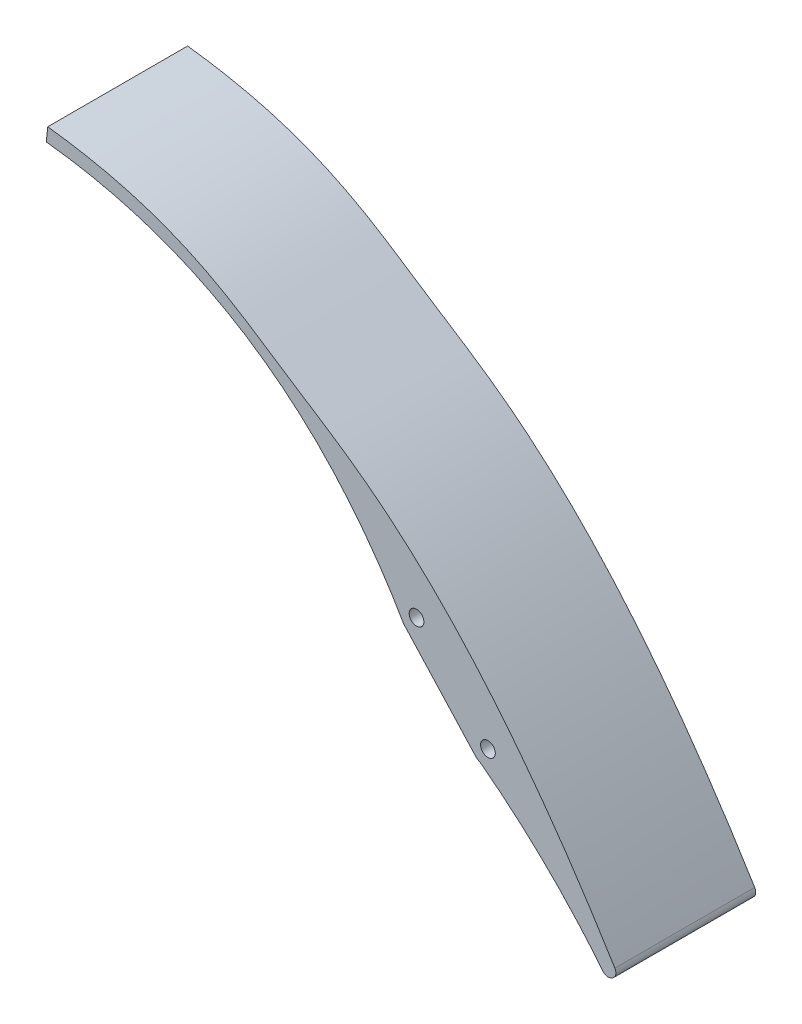
SolidWorks part; units mm, degrees
ref_plane "Front Plane" through (0, 0, 0) normal (0, 0, 1) x (1, 0, 0)
ref_plane "Top Plane" through (0, 0, 0) normal (0, 1, 0) x (1, 0, 0)
ref_plane "Right Plane" through (0, 0, 0) normal (1, 0, 0) x (0, 0, -1)
sketch "Sketch1" plane through (0, 0, 0) normal (0, 0, 1) x (1, 0, 0)
  line L0 (106.6087, -27.4995) -> (127.0352, -49.8278)
  line L2 (4.8232, 44.7408) -> (4.3944, 40.7638)
  line L4 (164.6351, -86.3417) -> (168.0847, -84.3173)
  circle A1 centre (110.2978, -24.1246) radius 5 construction
  arc A2 (127.0352, -49.8278) -> (128.7434, -51.0437) centre (130.7244, -46.4529) ccw
  circle A3 centre (0, 0) radius 43 construction
  circle A4 centre (130.7244, -46.4529) radius 1.7
  circle A5 centre (110.2978, -24.1246) radius 1.7
  spline S0 degree 2 poles (128.7434, -51.0437) (148.9684, -66.4337) (164.6351, -86.3417) knots 0 0 0 1 1 1
  spline S1 degree 3 poles (189.3837, -130.5798) (184.3453, -120.881) (179.1472, -111.2808) (168.3321, -92.3393) (162.7164, -82.997) (153.8589, -69.2518) (150.8335, -64.7151) (144.6059, -55.7509) (141.4039, -51.3233) (136.4366, -44.7833) (134.7529, -42.6197) (131.3384, -38.3486) (129.606, -36.2389) (124.3253, -29.9956) (120.6937, -25.9476) (113.1567, -18.1334) (109.2505, -14.368) (103.1437, -8.9743) (101.0669, -7.2188) (96.828, -3.7955) (94.6657, -2.128) (90.2629, 1.1268) (88.0206, 2.7142) (83.4948, 5.8371) (81.2164, 7.3742) (76.6483, 10.4306) (74.3592, 11.9509) (69.7972, 15.0169) (67.5211, 16.5576) (62.9312, 19.5797) (60.6175, 21.0615) (55.9207, 23.9157) (53.5376, 25.2883) (49.8952, 27.2409) (48.668, 27.875) (46.1993, 29.1003) (44.9585, 29.6912) (41.2169, 31.3965) (38.6963, 32.4435) (31.0559, 35.3128) (25.8568, 36.8621) (15.2645, 39.2915) (9.8717, 40.1734) (4.3944, 40.7638) knots 0 0 0 0 0.125 0.125 0.25 0.25 0.3125 0.3125 0.375 0.375 0.40625 0.40625 0.4375 0.4375 0.5 0.5 0.5625 0.5625 0.59375 0.59375 0.625 0.625 0.65625 0.65625 0.6875 0.6875 0.71875 0.71875 0.75 0.75 0.78125 0.78125 0.8125 0.8125 0.828125 0.828125 0.84375 0.84375 0.875 0.875 0.9375 0.9375 1 1 1 1 construction
  spline S2 degree 3 poles (4.8232, 44.7408) (41.6841, 40.2045) (60.0163, 25.5499) (92.1543, 5.4065) (129.8564, -21.2508) (168.0847, -84.3173) knots 0 0 0 0 0.536055 0.636055 1 1 1 1
  spline S4 degree 2 poles (4.3944, 40.7638) (71.4407, 33.3324) (106.6087, -27.4995) knots 0 0 0 1 1 1
  spline S5 degree 3 poles (4.8232, 44.7408) (39.4666, 41.0061) (63.7182, 23.7064) (102.0622, -1.507) (143.1831, -32.9689) (192.9333, -128.7358) knots 0 0 0 0 0.393439 0.493439 1 1 1 1 construction
  dimension "D1" = 86
  dimension "D2" = 10
  dimension "D3" = 10
  dimension "D4" = 3.4
  dimension "D5" = 3.4
extrude "Boss-Extrude1" add sketch "Sketch1" along normal blind 40
fillet "Fillet1" radius 2 2 edges at (164.6351, -86.3417, 20) (168.0847, -84.3173, 20)
sketch "Sketch2" plane through (0, 0, 40) normal (0, 0, 1) x (1, 0, 0)
  circle A0 centre (110.2978, -24.1246) radius 2.1
  circle A1 centre (130.7244, -46.4529) radius 2.1
  dimension "D1" = 4.2
  dimension "D2" = 4.2
extrude "Cut-Extrude1" cut sketch "Sketch2" against normal blind 5.7
ref_plane "Plane1" through (0, 0, 20) normal (0, 0, 1) x (1, 0, 0)
mirror "Mirror1" about plane through (0, 0, 20) normal (0, 0, 1) of "Cut-Extrude1"
